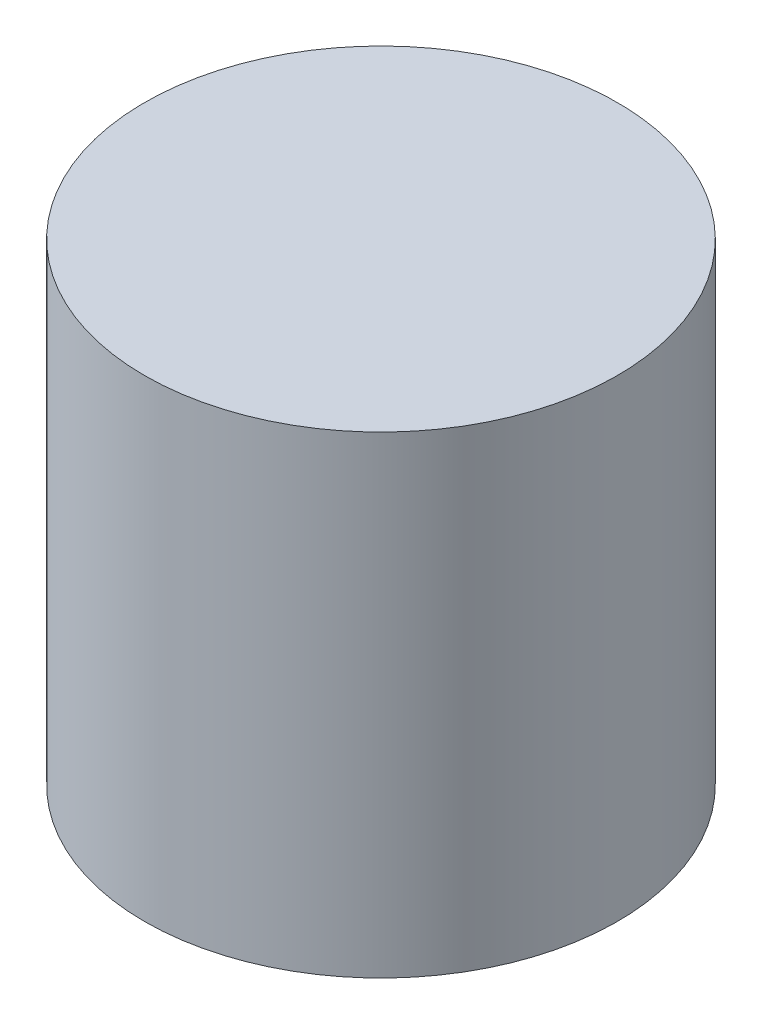
SolidWorks part; units mm, degrees
ref_plane "Plan de face" through (0, 0, 0) normal (0, 0, 1) x (1, 0, 0)
ref_plane "Plan de dessus" through (0, 0, 0) normal (0, 1, 0) x (1, 0, 0)
ref_plane "Plan de droite" through (0, 0, 0) normal (1, 0, 0) x (0, 0, -1)
sketch "Esquisse3" plane through (0, 0, 0) normal (0, 1, 0) x (1, 0, 0)
  circle A0 centre (0, 0) radius 2
  dimension "D1" = 4
extrude "Boss.-Extru.1" add sketch "Esquisse3" along normal blind 4
